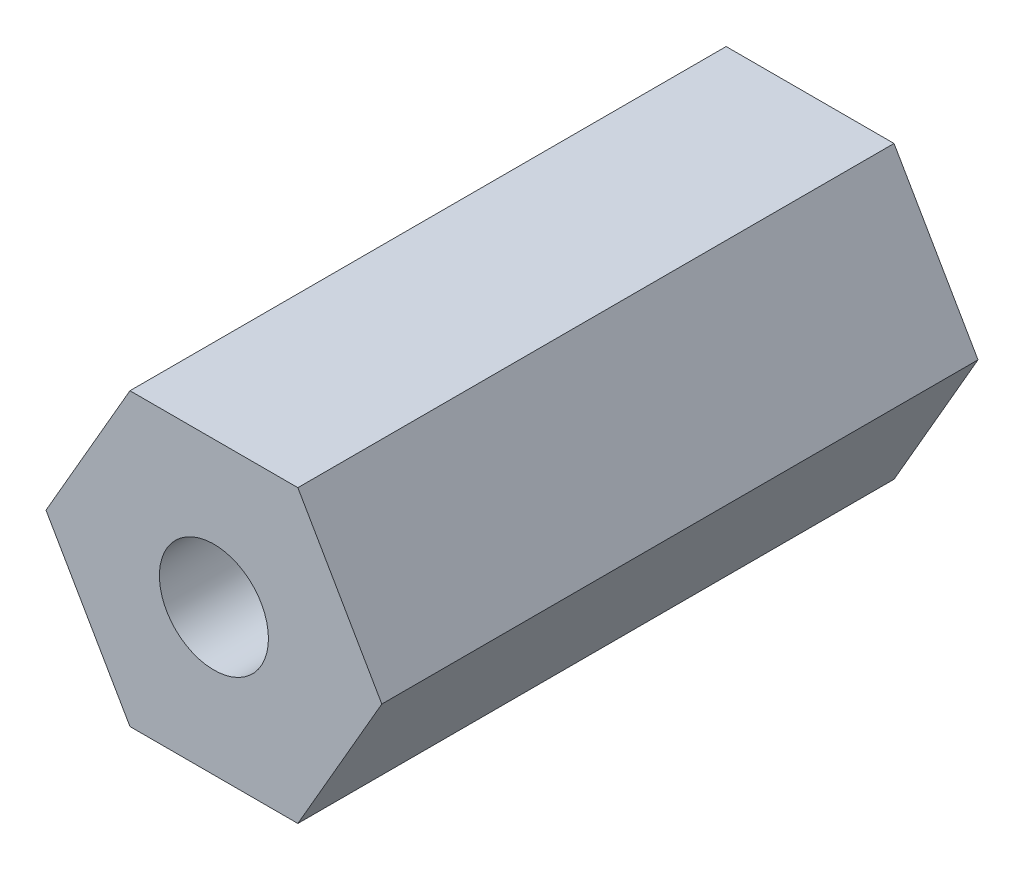
SolidWorks part; units mm, degrees
material "Chrome Stainless Steel"
ref_plane "Front" through (0, 0, 0) normal (0, 0, 1) x (1, 0, 0)
ref_plane "Top" through (0, 0, 0) normal (0, 1, 0) x (1, 0, 0)
ref_plane "Right" through (0, 0, 0) normal (1, 0, 0) x (0, 0, -1)
sketch "Sketch1" plane through (0, 0, 0) normal (0, 0, 1) x (1, 0, 0)
  line L1 (14.6647, 0) -> (7.3323, 12.7)
  line L2 (7.3323, 12.7) -> (-7.3323, 12.7)
  line L3 (-7.3323, 12.7) -> (-14.6647, 0)
  line L4 (-14.6647, 0) -> (-7.3323, -12.7)
  line L5 (-7.3323, -12.7) -> (7.3323, -12.7)
  line L6 (7.3323, -12.7) -> (14.6647, 0)
  circle A0 centre (0, 0) radius 12.7 construction
extrude "Extrude1" add sketch "Sketch1" along normal blind 52.07
hole_wizard "3/8-16 Tapped Hole1" positions "3DSketch1" profile "Sketch2" tap size "3/8-16" standard "Superior" end condition through all
sketch3d "3DSketch1"
  point P0 (0, 0, 52.07)
sketch "Sketch2" plane through (0, 0, 52.07) normal (1, 0, 0) x (0, -1, 0)
  line L0 (0, 0) -> (0, 52.07)
  line L1 (0, 52.07) -> (4.7625, 52.07)
  line L2 (4.7625, 52.07) -> (4.7625, 0)
  line L5 (4.7625, 0) -> (0, 0)
  line L11 (0, -6.35) -> (0, 107.95) construction
  dimension "Thread Major Dia." = 9.525
  dimension "Thru Tap Drill Depth" = 52.07
